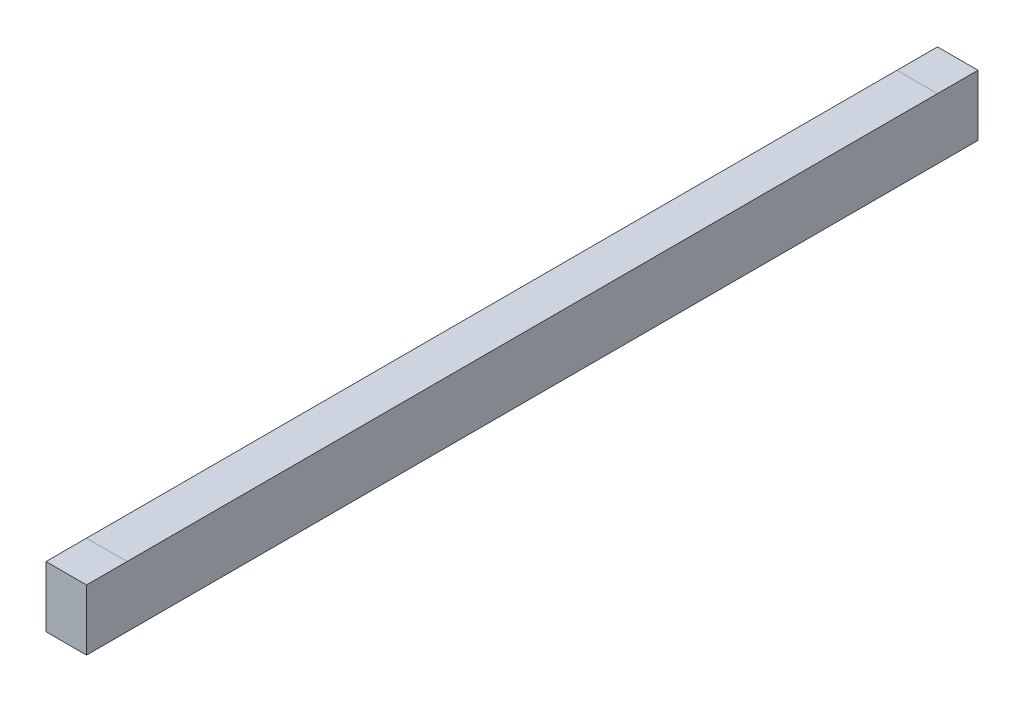
SolidWorks part; units mm, degrees
ref_plane "Płaszczyzna przednia" through (0, 0, 0) normal (0, 0, 1) x (1, 0, 0)
ref_plane "Płaszczyzna górna" through (0, 0, 0) normal (0, 1, 0) x (1, 0, 0)
ref_plane "Płaszczyzna prawa" through (0, 0, 0) normal (1, 0, 0) x (0, 0, -1)
sketch "Szkic1" plane through (0, 0, 0) normal (0, 0, 1) x (1, 0, 0)
  line L1 (0, 0) -> (100, 0)
  line L2 (0, 0) -> (0, 150)
  line L3 (0, 150) -> (100, 150)
  line L4 (100, 0) -> (100, 150)
  dimension "D1" = 150
  dimension "D2" = 100
extrude "Dodanie-wyciągnięcie1" add sketch "Szkic1" along normal blind 2200
sketch "Szkic2" plane through (0, 0, 0) normal (0, 1, 0) x (1, 0, 0)
  line L0 (0, -2100) -> (100, -2100)
  line L1 (0, -2200) -> (0, 0) construction
  line L2 (100, -2200) -> (100, 0) construction
  line L3 (0, -100) -> (100, -100)
  line L4 (100, 0) -> (0, 0) construction
  line L5 (100, -2200) -> (0, -2200) construction
  dimension "D1" = 100
  dimension "D2" = 100
split line "Linia podziałowa2"
